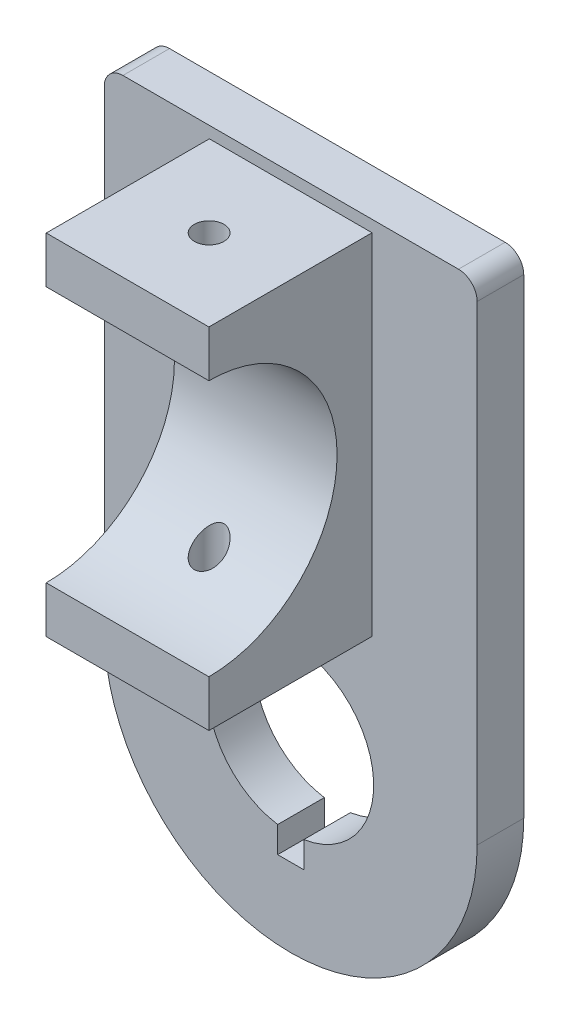
SolidWorks part; units mm, degrees
material "PET"
ref_plane "Front Plane" through (0, 0, 0) normal (0, 0, 1) x (1, 0, 0)
ref_plane "Top Plane" through (0, 0, 0) normal (0, 1, 0) x (1, 0, 0)
ref_plane "Right Plane" through (0, 0, 0) normal (1, 0, 0) x (0, 0, -1)
sketch "Sketch1" plane through (0, 0, 0) normal (0, 0, 1) x (1, 0, 0)
  line L7 (0, 0) -> (0, 64.135)
  line L8 (2.54, 66.675) -> (48.26, 66.675)
  line L9 (50.8, 64.135) -> (50.8, 0)
  line L10 (25.4, 0) -> (25.4, -14.7183) construction
  line L11 (23.622, -11.1623) -> (23.622, -14.7183)
  line L12 (23.622, -14.7183) -> (27.178, -14.7183)
  line L13 (27.178, -14.7183) -> (27.178, -11.1623)
  arc A4 (50.8, 0) -> (0, 0) centre (25.4, 0) cw
  arc A5 (27.178, -11.1623) -> (23.622, -11.1623) centre (25.4, 0) ccw
  arc A6 (48.26, 66.675) -> (50.8, 64.135) centre (48.26, 64.135) cw
  arc A7 (0, 64.135) -> (2.54, 66.675) centre (2.54, 64.135) cw
  point P10 (50.8, 66.675)
  point P15 (0, 66.675)
  dimension "D3" = 22.606
  dimension "D4" = 3.556
  dimension "D5" = 1.778
  dimension "D7" = 2.54
  dimension "D1" = 66.675
  dimension "D2" = 50.8
  dimension "D6" = 1.778
extrude "Boss-Extrude1" add sketch "Sketch1" along normal blind 6.35
sketch "Sketch2" plane through (0, 0, 6.35) normal (0, 0, 1) x (1, 0, 0)
  line L1 (14.3192, 17.4625) -> (36.4808, 17.4625)
  line L2 (14.3192, 17.4625) -> (14.3192, 65.0875)
  line L3 (14.3192, 65.0875) -> (36.4808, 65.0875)
  line L4 (36.4808, 17.4625) -> (36.4808, 65.0875)
  line L7 (48.26, 66.675) -> (2.54, 66.675) construction
  line L8 (25.4, 17.4625) -> (25.4, 65.0875) construction
  point P8 (25.4, 66.675)
  dimension "D1" = 22.1615
  dimension "D2" = 47.625
  dimension "D4" = 1.5875
extrude "Boss-Extrude2" add sketch "Sketch2" along normal blind 22.225 separate body
sketch "Sketch3" plane through (14.3192, 0, 0) normal (-1, 0, 0) x (0, 0, 1)
  line L2 (28.575, 65.0875) -> (28.575, 17.4625) construction
  line L3 (28.575, 17.4625) -> (6.35, 17.4625) construction
  arc A1 (28.575, 23.8125) -> (28.575, 58.7375) centre (28.575, 41.275) cw
  dimension "D1" = 6.35
extrude "Cut-Extrude1" cut sketch "Sketch3" against normal through all and the other way through all flip side to cut
hole_wizard "#10-32 Tapped Hole1" positions "Sketch7" profile "Sketch6" tap size "#10-32" standard "ANSI Inch" end condition up to next
sketch "Sketch7" plane through (0, 65.0875, 0) normal (0, 1, 0) x (1, 0, 0)
  line L4 (14.3192, -17.4625) -> (36.4808, -17.4625) construction
  line L5 (14.3192, -28.575) -> (14.3192, -6.35) construction
  line L6 (36.4808, -28.575) -> (36.4808, -6.35) construction
  point P0 (25.4, -17.4625)
  point P33 (0, 0)
  point P34 (25.4, -17.4625)
sketch "Sketch6" plane through (25.4, 65.0875, 17.4625) normal (1, 0, 0) x (0, 0, 1)
  line L0 (0, 0) -> (0, 23.8125)
  line L1 (0, 23.8125) -> (2.0193, 23.8125)
  line L2 (2.0193, 23.8125) -> (2.0193, 0)
  line L5 (2.0193, 0) -> (0, 0)
  line L11 (0, -6.35) -> (0, 107.95) construction
  dimension "Thru Tap Drill Dia." = 4.0386
  dimension "Thru Tap Drill Depth" = 23.8125
cosmetic thread "Hole Thread1" parameters "D2"=4.826
hole_wizard "#10-32 Tapped Hole2" positions "Sketch8" profile "Sketch9" tap size "#10-32" standard "ANSI Inch" end condition up to next
sketch "Sketch8" plane through (0, 17.4625, 0) normal (0, -1, 0) x (-1, 0, 0)
  point P22 (-25.4, -17.4625)
sketch "Sketch9" plane through (25.4, 17.4625, 17.4625) normal (1, 0, 0) x (0, 0, -1)
  line L0 (0, 0) -> (0, 41.276)
  line L1 (0, 41.276) -> (2.0193, 41.276)
  line L2 (2.0193, 41.276) -> (2.0193, 0)
  line L5 (2.0193, 0) -> (0, 0)
  line L11 (0, -6.35) -> (0, 107.95) construction
  dimension "Thru Tap Drill Dia." = 4.0386
  dimension "Thru Tap Drill Depth" = 41.276
cosmetic thread "Hole Thread2" parameters "D1"=13.2366, "D2"=5.0386
